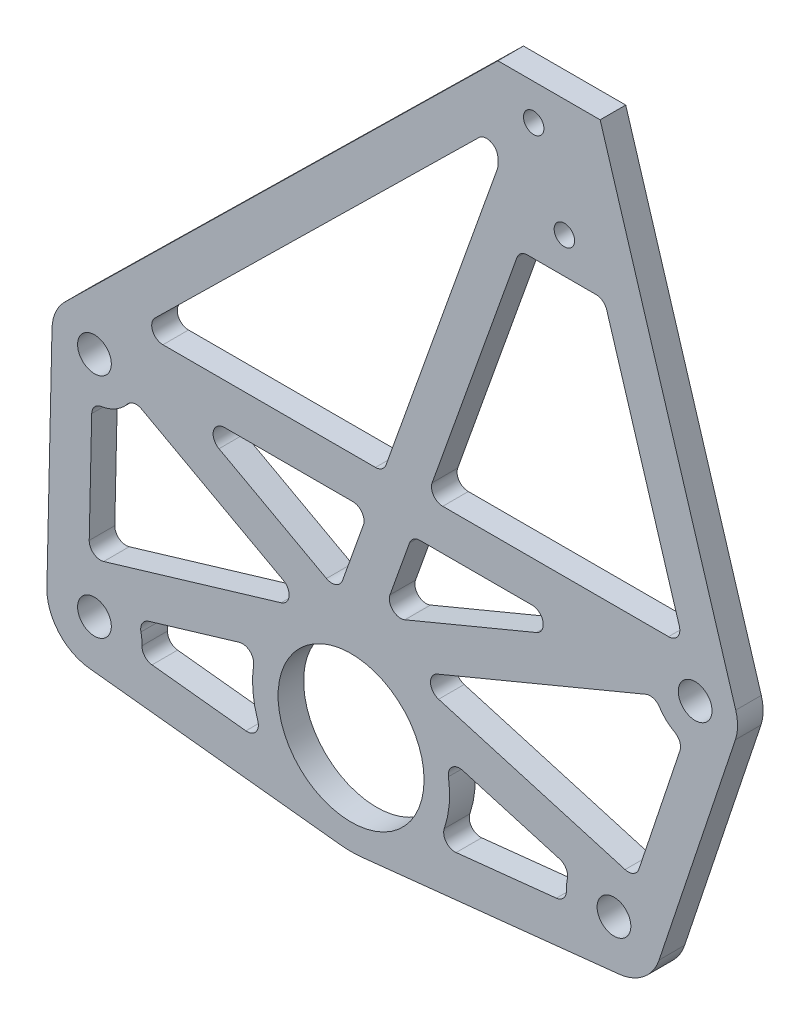
SolidWorks part; units mm, degrees
ref_plane "Front Plane" through (0, 0, 0) normal (0, 0, 1) x (1, 0, 0)
ref_plane "Top Plane" through (0, 0, 0) normal (0, 1, 0) x (1, 0, 0)
ref_plane "Right Plane" through (0, 0, 0) normal (1, 0, 0) x (0, 0, -1)
sketch "Sketch1" plane through (0, 0, 0) normal (0, 0, 1) x (1, 0, 0)
  line L0 (-57.4678, 40.1672) -> (-58.4676, -4.2603)
  line L1 (-50.1739, -13.717) -> (-1.0667, -19.0593)
  line L2 (3.0522, -19.0647) -> (53.4138, -13.7196)
  line L3 (61.2565, -7.4119) -> (76.1828, 37.3544)
  line L4 (55.0306, 4.4621) -> (6.4024, 18.6099)
  line L5 (49.7321, 99.1304) -> (42.7321, 99.1304) construction
  line L6 (49.7321, 99.1304) -> (49.7321, 106.1304) construction
  line L7 (49.7321, 106.1304) -> (42.7321, 106.1304) construction
  line L8 (49.7321, 129.1304) -> (29.7321, 129.1304)
  line L9 (49.7321, 129.1304) -> (76.2463, 42.4077)
  line L10 (33.9793, 99.1304) -> (15.8259, 48.2824)
  line L11 (-1.5338, 23.451) -> (6.9607, 23.451) construction
  line L12 (49.7321, 129.1304) -> (49.7321, 99.1304)
  line L13 (29.7321, 129.1304) -> (29.7321, 99.1304)
  line L14 (29.7321, 99.1304) -> (50.5386, 99.1304)
  line L16 (42.7321, 99.1304) -> (42.7321, 106.1304) construction
  line L21 (-54.986, 45.9027) -> (29.7321, 129.1304)
  line L22 (36.7321, 122.1304) -> (29.7321, 122.1304) construction
  line L23 (36.7321, 122.1304) -> (36.7321, 129.1304) construction
  line L24 (36.7321, 129.1304) -> (29.7321, 129.1304) construction
  line L25 (29.7321, 122.1304) -> (29.7321, 129.1304) construction
  line L26 (61.2871, 17.9305) -> (68.7196, 14.9713) construction
  line L27 (65.1182, 47.6456) -> (-6.3857, 17.8986)
  line L28 (17.7537, -9.4594) -> (43.4105, -6.7364)
  line L29 (30.5821, -8.0979) -> (31.4264, -16.0532) construction
  line L30 (31.5652, 2.9574) -> (33.8, 10.6389) construction
  line L31 (12.1394, 16.9407) -> (60.531, 37.0725)
  line L32 (36.3352, 27.0066) -> (33.2624, 34.393) construction
  line L33 (43.952, -0.6464) -> (19.1783, 6.5612)
  line L34 (-43.2556, 46.2121) -> (2.1413, 21.446)
  line L35 (-49.6565, 31.6928) -> (-50.2624, 4.7678)
  line L36 (-40.1523, -6.76) -> (-15.743, -9.4155)
  line L37 (-27.9477, -8.0878) -> (-28.8129, -16.0408) construction
  line L38 (56.5923, 3.8503) -> (65.9818, 32.0107)
  line L39 (-49.9594, 18.2303) -> (-57.9574, 18.4103) construction
  line L40 (-41.7401, 36.2722) -> (-7.3063, 17.4871)
  line L41 (-20.5571, 33.8291) -> (-24.3884, 26.8062) construction
  line L42 (-7.5975, 17.646) -> (-50.2591, 4.9122)
  line L43 (62.9892, 85.7691) -> (55.3388, 83.4301) construction
  line L44 (29.7321, 117.9158) -> (-43.4612, 46.0101)
  line L45 (66.1483, 48.0741) -> (50.5386, 99.1304)
  line L46 (-6.8646, 81.9629) -> (-12.471, 87.6698) construction
  line L47 (-17.187, 6.4349) -> (-40.7146, -0.5877)
  line L48 (-31.2389, 10.5894) -> (-28.9508, 2.9236) construction
  line L49 (-41.1482, 48.2824) -> (66.0847, 48.2824)
  line L50 (-32.3864, 40.2824) -> (47.4191, 40.2824)
  line L51 (12.4682, 48.2824) -> (12.4682, 40.2824) construction
  line L52 (6.9607, 23.451) -> (12.9698, 40.2824)
  line L53 (22.6263, 79.2271) -> (29.7321, 99.1304) construction
  line L54 (29.7321, 111.0271) -> (7.3313, 48.2824)
  line L55 (4.4752, 40.2824) -> (-1.5338, 23.451)
  line L56 (26.3934, 77.8822) -> (18.8592, 80.572) construction
  arc A0 (1.0179, 14.3772) -> (1.0179, -14.1724) centre (1.0179, 0.1024) ccw
  arc A1 (1.0179, -14.1724) -> (1.0179, 14.3772) centre (1.0179, 0.1024) ccw
  arc A2 (68.3071, 43.2824) -> (68.3071, 36.6784) centre (68.3071, 39.9804) ccw
  arc A3 (68.3071, 36.6784) -> (68.3071, 43.2824) centre (68.3071, 39.9804) ccw
  arc A4 (-49.1679, 36.6784) -> (-49.1679, 43.2824) centre (-49.1679, 39.9804) ccw
  arc A5 (-49.1679, 43.2824) -> (-49.1679, 36.6784) centre (-49.1679, 39.9804) ccw
  arc A6 (-49.1679, -1.1676) -> (-49.1679, -7.7716) centre (-49.1679, -4.4696) ccw
  arc A7 (-49.1679, -7.7716) -> (-49.1679, -1.1676) centre (-49.1679, -4.4696) ccw
  arc A8 (52.4321, -1.1676) -> (52.4321, -7.7716) centre (52.4321, -4.4696) ccw
  arc A9 (52.4321, -7.7716) -> (52.4321, -1.1676) centre (52.4321, -4.4696) ccw
  circle A20 centre (36.7321, 122.1304) radius 2
  circle A21 centre (42.7321, 106.1304) radius 2
  circle A27 centre (-49.1679, 39.9804) radius 8.302
  circle A28 centre (68.3071, 39.9804) radius 8.302
  circle A29 centre (52.4321, -4.4696) radius 9.302
  circle A30 centre (-49.1679, -4.4696) radius 9.302
  circle A31 centre (1.0179, 0.1024) radius 19.2748
  point P103 (2.7135, 23.451)
  dimension "D2" = 4
  dimension "D1" = 5
  dimension "D5" = 5
  dimension "D3" = 7
  dimension "D6" = 6
  dimension "D10" = 8
  dimension "D4" = 30
  dimension "D7" = 20
  dimension "D8" = 80.848
  dimension "D9" = 44.492
extrude "Boss-Extrude1" add sketch "Sketch1" along normal blind 5
fillet "Fillet1" radius 2.2 30 edges at (43.952, -0.6464, 2.5) (43.4105, -6.7364, 2.5) (-40.1523, -6.76, 2.5) (-40.7146, -0.5877, 2.5) (-41.1482, 48.2824, 2.5) (7.3313, 48.2824, 2.5) (66.0847, 48.2824, 2.5) (6.9607, 23.451, 2.5) (47.4191, 40.2824, 2.5) (-49.6565, 31.6928, 2.5) (-41.7401, 36.2722, 2.5) (-50.2591, 4.9122, 2.5) (-32.3864, 40.2824, 2.5) (4.4752, 40.2824, 2.5) (12.9698, 40.2824, 2.5) (12.1394, 16.9407, 2.5) (60.531, 37.0725, 2.5) (65.9818, 32.0107, 2.5) (56.5923, 3.8503, 2.5) (17.7537, -9.4594, 2.5) (19.1783, 6.5612, 2.5) (-15.743, -9.4155, 2.5) (-17.187, 6.4349, 2.5) (-7.5975, 17.646, 2.5) (-1.5338, 23.451, 2.5) (33.9793, 99.1304, 2.5) (15.8259, 48.2824, 2.5) (50.5386, 99.1304, 2.5) (29.7321, 117.9158, 2.5) (29.7321, 111.0271, 2.5)
sketch "Sketch2" [suppressed] plane through (0, 0, 0) normal (0, 0, 1) x (1, 0, 0)
  line L5 (-78.2721, 120.7172) -> (-49.6921, 120.7172) construction
  line L6 (-57.5176, 37.9571) -> (-88.9426, 95.7567)
  line L8 (-88.9426, 95.7567) -> (-88.9426, 145.6777)
  line L10 (-39.0216, 145.6777) -> (-88.9426, 145.6777)
  line L12 (29.7321, 129.1304) -> (49.7321, 129.1304)
  line L13 (-54.986, 45.9027) -> (29.7321, 129.1304)
  line L14 (-39.0216, 145.6777) -> (49.7321, 129.1304)
  line L15 (-39.0216, 137.5399) -> (-39.0216, 95.7567)
  line L16 (-39.0216, 95.7567) -> (-79.4929, 95.7567)
  line L17 (-79.4929, 95.7567) -> (-53.2924, 47.5665)
  line L18 (-39.0216, 95.7567) -> (-40.1865, 60.4419)
  line L19 (-47.3281, 95.7567) -> (-48.7712, 52.0082)
  line L20 (-54.986, 45.9027) -> (29.7321, 129.1304) construction
  line L22 (-39.0216, 95.7567) -> (13.1171, 112.8077)
  line L23 (-39.0216, 137.5399) -> (17.4969, 127.0025)
  line L26 (-10.7623, 132.2712) -> (-9.2961, 140.1357) construction
  line L27 (26.3934, 77.8822) -> (18.8592, 80.572) construction
  line L28 (-39.0216, 104.1737) -> (17.7776, 122.7488)
  line L29 (-12.9523, 104.2822) -> (-15.4389, 111.8859) construction
  line L30 (-57.5176, 37.9571) -> (-57.4699, 39.9804)
  line L31 (-57.4678, 40.1672) -> (-58.4676, -4.2603) construction
  arc A0 (17.7776, 122.7488) -> (17.4969, 127.0025) centre (17.0937, 124.8398) ccw
  circle A1 centre (-81.9426, 138.6777) radius 2.0193
  circle A2 centre (-63.9821, 120.7172) radius 14.29
  circle A3 centre (-46.0216, 102.7567) radius 2.0193
  circle A4 centre (-46.0216, 138.6777) radius 2.0193
  circle A5 centre (-81.9426, 102.7567) radius 2.0193
  circle A6 centre (-49.1679, 39.9804) radius 8.302 construction
  arc A7 (-54.986, 45.9027) -> (-57.4699, 39.9804) centre (-49.1679, 39.9804) ccw
  point P16 (-63.9821, 120.7172)
  point P22 (25.96, 125.4247)
  dimension "D1" = 4.0386
  dimension "D2" = 81.9426
  dimension "D3" = 138.6777
  dimension "D4" = 35.921
  dimension "D8" = 28.58
  dimension "D13" = 2.2
  dimension "D5" = 35.921
  dimension "D6" = 120.7172
  dimension "D7" = 63.9821
  dimension "D9" = 7
  dimension "D10" = 7
  dimension "D11" = 7
  dimension "D12" = 7
extrude "Boss-Extrude2" [suppressed] add sketch "Sketch2" along normal up to vertex (5 mm away) contours L28 L15 L22 L13 | L16 L19 L13 L18
fillet "Fillet2" [suppressed] radius 2.2
equation "\"D5@Sketch1\"=\"D1@Sketch1\""
